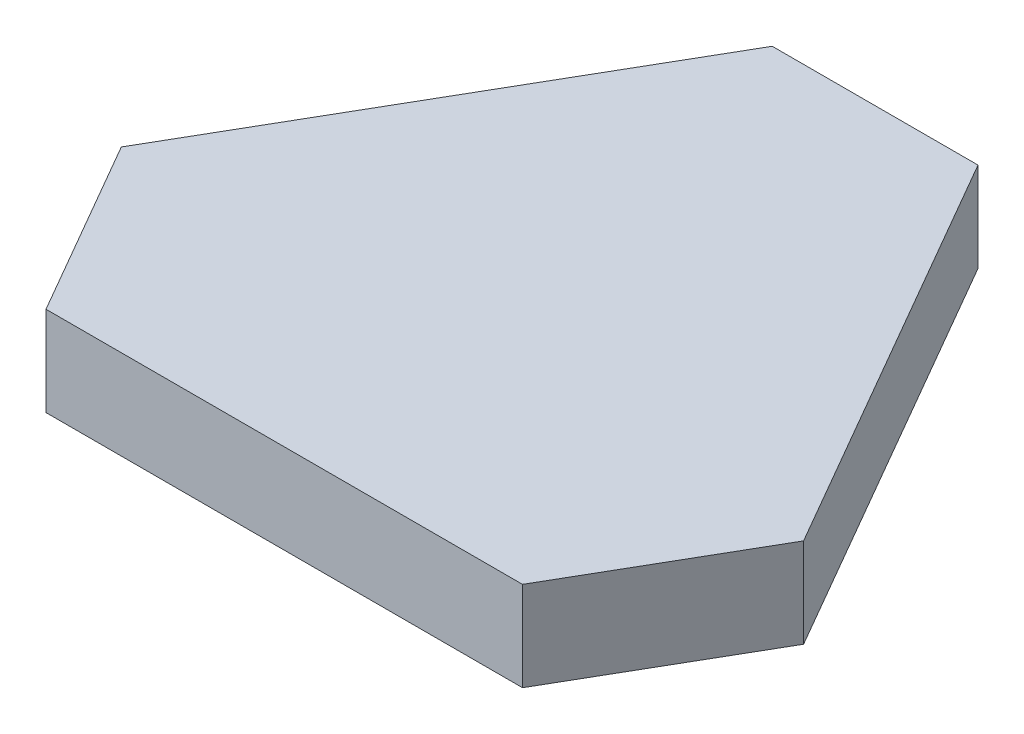
SolidWorks part; units mm, degrees
ref_plane "前基準面" through (0, 0, 0) normal (0, 0, 1) x (1, 0, 0)
ref_plane "上基準面" through (0, 0, 0) normal (0, 1, 0) x (1, 0, 0)
ref_plane "右基準面" through (0, 0, 0) normal (1, 0, 0) x (0, 0, -1)
sketch "草圖1" plane through (0, 0, 0) normal (0, 1, 0) x (1, 0, 0)
  line L0 (-90.1222, 0) -> (90.1222, 0)
  line L1 (90.1222, 0) -> (165.1222, 129.9038)
  line L2 (165.1222, 129.9038) -> (75, 286)
  line L3 (75, 286) -> (-75, 286)
  line L4 (-75, 286) -> (-165.1222, 129.9038)
  line L5 (-165.1222, 129.9038) -> (-90.1222, 0)
  dimension "D1" = 286
  dimension "D2" = 286
  dimension "D3" = 286
  dimension "D4" = 150
  dimension "D5" = 60
extrude "填料-伸長1" add sketch "草圖1" along normal blind 5
fillet "圓角1" radius 20 6 edges at (90.1222, 2.5, 0) (-90.1222, 2.5, 0) (-165.1222, 2.5, -129.9038) (-75, 2.5, -286) (75, 2.5, -286) (165.1222, 2.5, -129.9038)
sketch "草圖2" plane through (0, 5, 0) normal (0, 1, 0) x (1, 0, 0)
  line L12 (-26.6136, 110) -> (26.6136, 110)
  line L13 (26.6136, 110) -> (38.1051, 129.9038)
  line L14 (38.1051, 129.9038) -> (11.4915, 176)
  line L15 (11.4915, 176) -> (-11.4915, 176)
  line L16 (-11.4915, 176) -> (-38.1051, 129.9038)
  line L17 (-38.1051, 129.9038) -> (-26.6136, 110)
  line L18 (-26.6136, 110) -> (26.6136, 110)
  line L19 (26.6136, 110) -> (38.1051, 129.9038)
  line L20 (38.1051, 129.9038) -> (11.4915, 176)
  line L21 (11.4915, 176) -> (-11.4915, 176)
  line L22 (-11.4915, 176) -> (-38.1051, 129.9038)
  line L23 (-38.1051, 129.9038) -> (-26.6136, 110)
  dimension "D1" = 110
extrude "填料-伸長2" add sketch "草圖2" along normal blind 10 contours L22 L23 L18 L19 L20 L21
sketch "草圖3" plane through (0, 5, 0) normal (0, 1, 0) x (1, 0, 0)
  line L1 (-217.5038, 303.3785) -> (241.3315, 303.3785)
  line L2 (-217.5038, 303.3785) -> (-217.5038, -22.2662)
  line L3 (-217.5038, -22.2662) -> (241.3315, -22.2662)
  line L4 (241.3315, 303.3785) -> (241.3315, -22.2662)
extrude "除料-伸長1" cut sketch "草圖3" against normal blind 10
ref_plane "平面1" through (0, 17, 0) normal (0, 1, 0) x (1, 0, 0)
